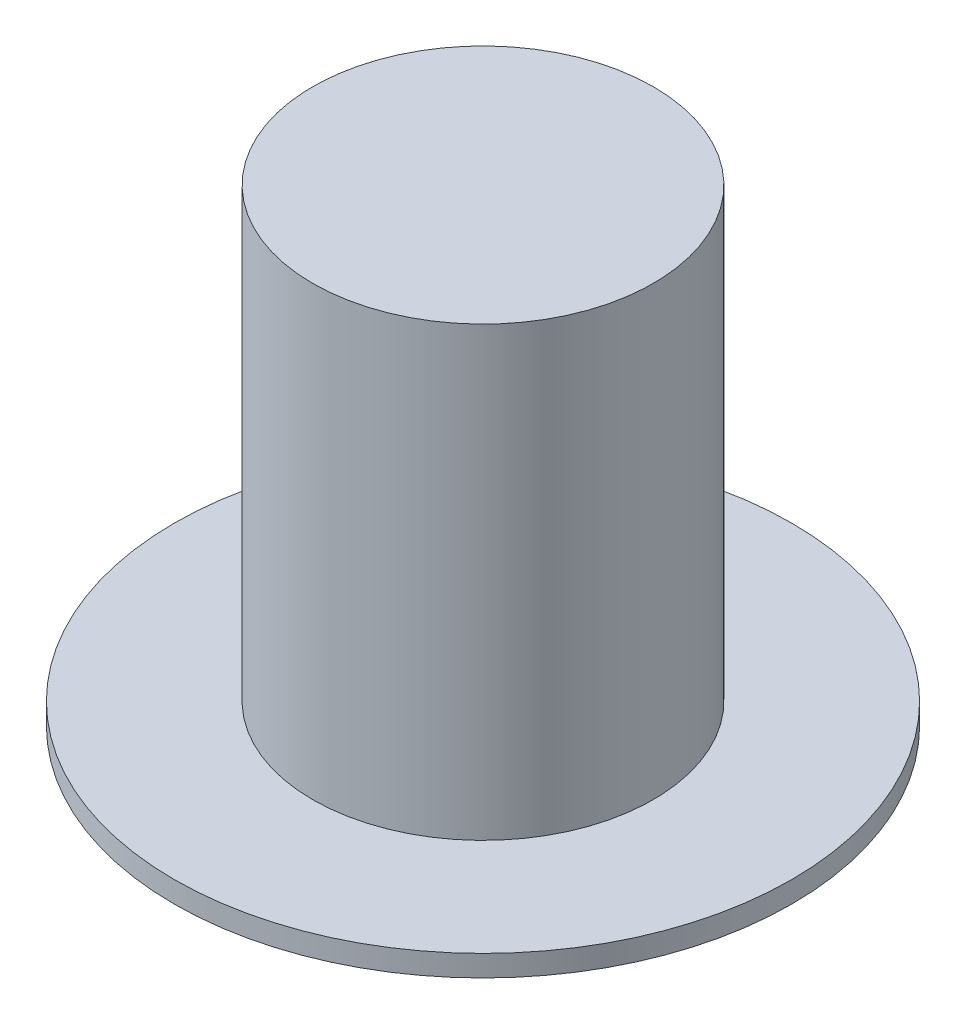
SolidWorks part; units mm, degrees
ref_plane "前视基准面" through (0, 0, 0) normal (0, 0, 1) x (1, 0, 0)
ref_plane "上视基准面" through (0, 0, 0) normal (0, 1, 0) x (1, 0, 0)
ref_plane "右视基准面" through (0, 0, 0) normal (1, 0, 0) x (0, 0, -1)
sketch "草图1" plane through (0, 0, 0) normal (0, 1, 0) x (1, 0, 0)
  circle A0 centre (0, 0) radius 14.5
  dimension "D1" = 29
extrude "拉伸1" add sketch "草图1" along normal blind 1
sketch "草图2" plane through (0, 1, 0) normal (0, 1, 0) x (-1, 0, 0)
  line L0 (-16.2338, 0) -> (18.7662, 0) construction
  line L1 (-17.5, -17.5) -> (17.5, -17.5)
  line L2 (-17.5, -17.5) -> (-17.5, 17.5)
  line L3 (-17.5, 17.5) -> (17.5, 17.5)
  line L4 (17.5, -17.5) -> (17.5, 17.5)
  line L5 (0, 22.2752) -> (0, -24.9896) construction
  dimension "D1" = 35
  dimension "D2" = 35
extrude "拉伸2" [suppressed] add sketch "草图2" along normal blind 15
sketch "草图3" plane through (0, 1, 0) normal (0, 1, 0) x (-1, 0, 0)
  circle A0 centre (0, 0) radius 8
  dimension "D1" = 16
extrude "拉伸3" add sketch "草图3" along normal blind 21
sketch "草图4" plane through (0, 0, 0) normal (0, 1, 0) x (-1, 0, 0)
  line L0 (0, -6.2238) -> (0, 5.8769) construction
  line L1 (4.0827, 0) -> (-3.4119, 0) construction
  line L3 (1, -6.5) -> (-1, -6.5)
  line L4 (1, -6.5) -> (1, 6.5)
  line L5 (1, 6.5) -> (-1, 6.5)
  line L6 (-1, -6.5) -> (-1, 6.5)
  dimension "D1" = 2
  dimension "D2" = 13
extrude "切除-拉伸1" cut sketch "草图4" along normal blind 10
sketch "草图5" plane through (0, 10, 0) normal (0, -1, 0) x (1, 0, 0)
  line L0 (-1, -6.5) -> (-1, 6.5) construction
  line L1 (-1, 1) -> (1, 1)
  line L2 (-1, 1) -> (-1, -1)
  line L3 (-1, -1) -> (1, -1)
  line L4 (1, 1) -> (1, -1)
  line L5 (1, 6.5) -> (1, -6.5) construction
  line L6 (2.2231, 0) -> (-1.9671, 0) construction
  dimension "D1" = 2
extrude "拉伸4" add sketch "草图5" along normal blind 1
